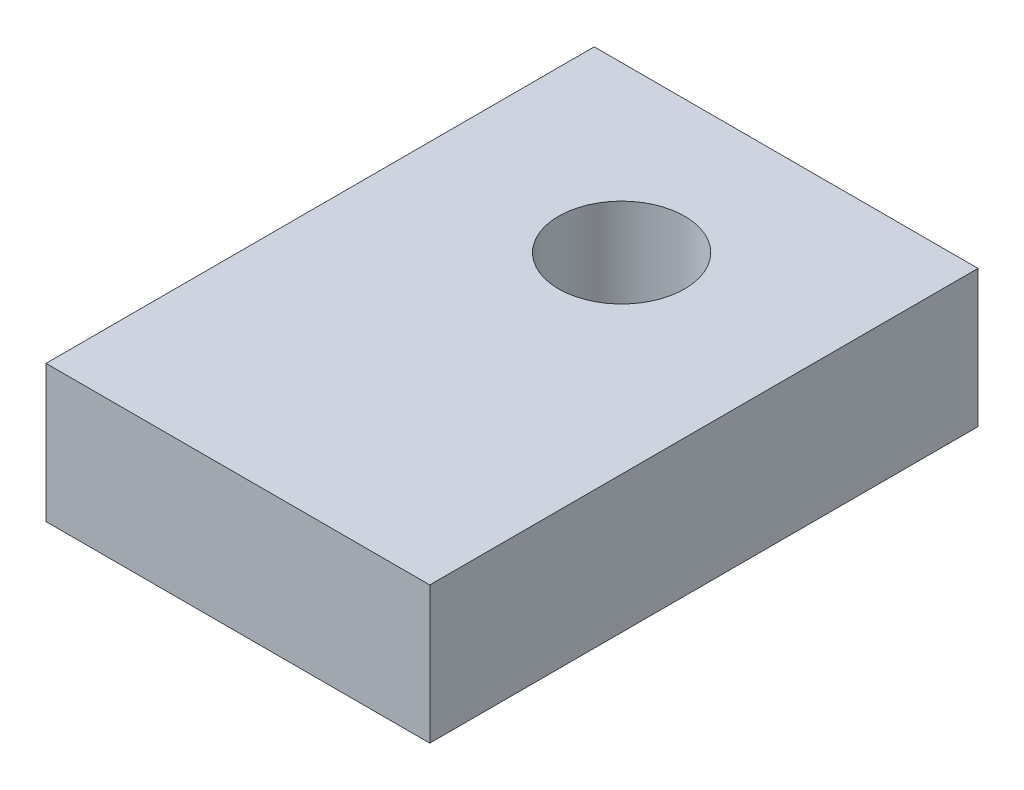
SolidWorks part; units mm, degrees
ref_plane "Front Plane" through (0, 0, 0) normal (0, 0, 1) x (1, 0, 0)
ref_plane "Top Plane" through (0, 0, 0) normal (0, 1, 0) x (1, 0, 0)
ref_plane "Right Plane" through (0, 0, 0) normal (1, 0, 0) x (0, 0, -1)
sketch "Sketch1" plane through (0, 0, 0) normal (0, 1, 0) x (1, 0, 0)
  line L1 (0, 0) -> (8.89, 0)
  line L2 (0, 0) -> (0, 12.7)
  line L3 (0, 12.7) -> (8.89, 12.7)
  line L4 (8.89, 0) -> (8.89, 12.7)
  circle A0 centre (4.445, 8.89) radius 1.4605
  dimension "D3" = 2.921
  dimension "D1" = 8.89
  dimension "D2" = 12.7
  dimension "D4" = 3.81
  dimension "D5" = 4.445
extrude "Boss-Extrude1" add sketch "Sketch1" along normal blind 3.175
